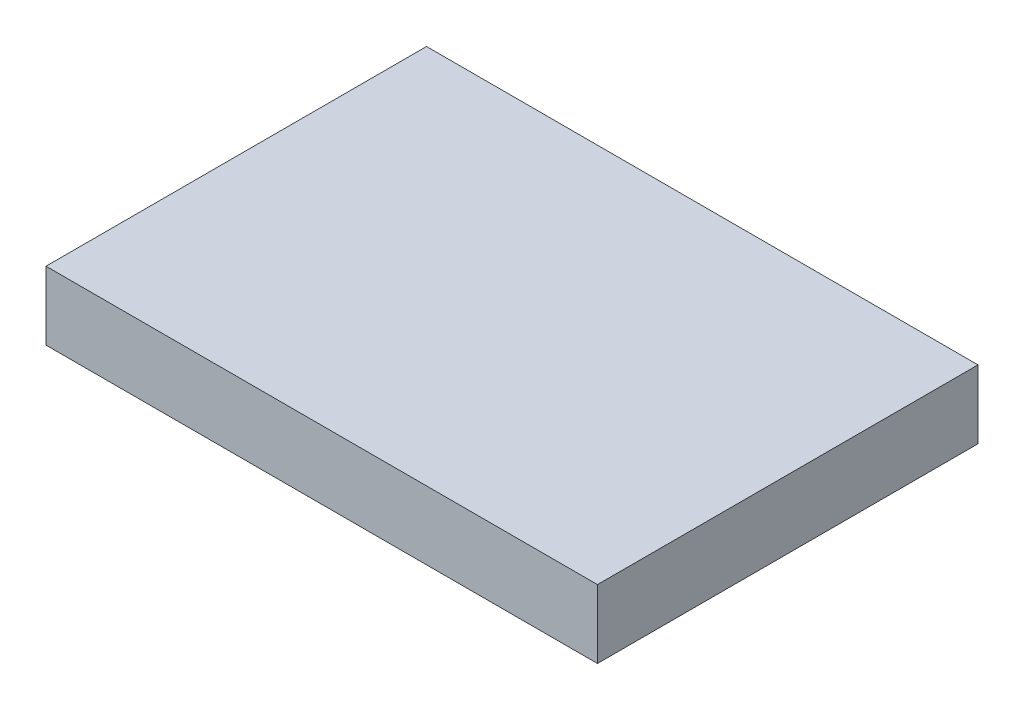
SolidWorks part; units mm, degrees
ref_plane "Front Plane" through (0, 0, 0) normal (0, 0, 1) x (1, 0, 0)
ref_plane "Top Plane" through (0, 0, 0) normal (0, 1, 0) x (1, 0, 0)
ref_plane "Right Plane" through (0, 0, 0) normal (1, 0, 0) x (0, 0, -1)
sketch "Sketch1" plane through (0, 0, 0) normal (0, 1, 0) x (1, 0, 0)
  line L1 (16.7, 368.6577) -> (631.38, 368.6577)
  line L2 (16.7, 368.6577) -> (16.7, -55.5223)
  line L3 (16.7, -55.5223) -> (631.38, -55.5223)
  line L4 (631.38, 368.6577) -> (631.38, -55.5223)
extrude "Boss-Extrude2" add sketch "Sketch1" along normal blind 76.2
